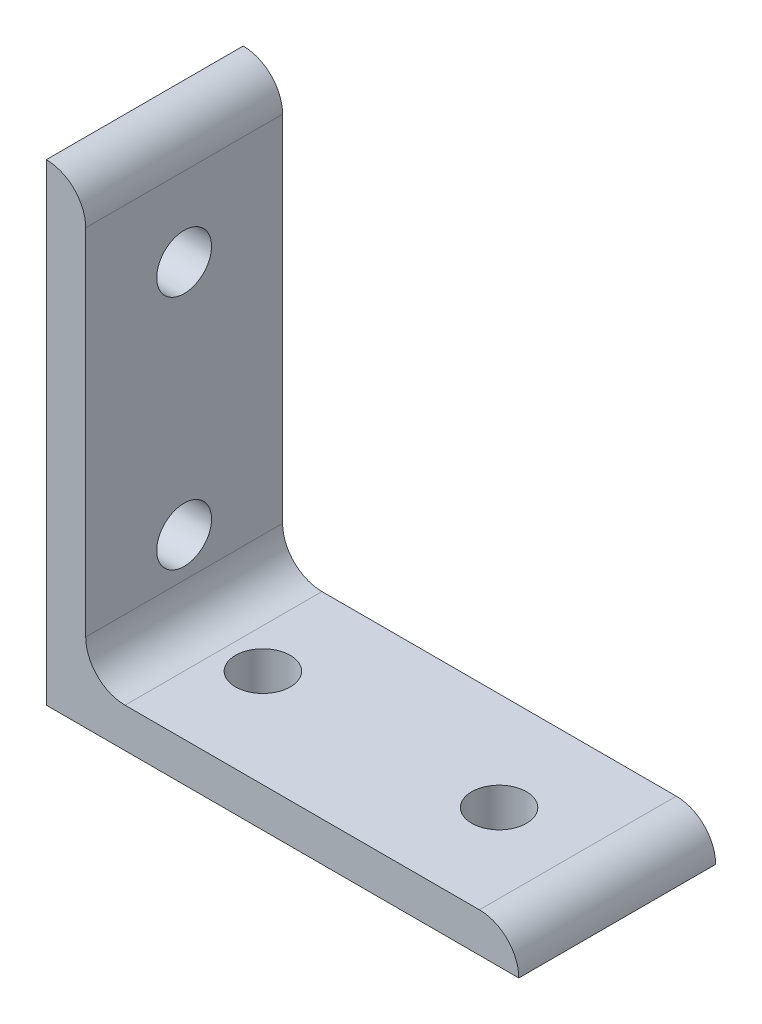
SolidWorks part; units mm, degrees
material "6061 Alloy"
ref_plane "Front Plane" through (0, 0, 0) normal (0, 0, 1) x (1, 0, 0)
ref_plane "Top Plane" through (0, 0, 0) normal (0, 1, 0) x (1, 0, 0)
ref_plane "Right Plane" through (0, 0, 0) normal (1, 0, 0) x (0, 0, -1)
sketch "Sketch1" plane through (0, 0, 0) normal (0, 0, 1) x (1, 0, 0)
  line L1 (0, 0) -> (76.2, 0)
  line L2 (0, 0) -> (0, 76.2)
  line L7 (69.85, 6.35) -> (6.35, 6.35)
  line L8 (6.35, 69.85) -> (6.35, 6.35)
  arc A0 (76.2, 0) -> (69.85, 6.35) centre (69.85, 0) ccw
  arc A1 (0, 76.2) -> (6.35, 69.85) centre (0, 69.85) cw
  dimension "D1" = 6.35
  dimension "D2" = 76.2
extrude "Boss-Extrude1" add sketch "Sketch1" along normal mid plane 31.75
hole_wizard "S (0.348) Diameter Hole1" positions "Sketch2" profile "Sketch3" hole size "S" standard "ANSI Inch" end condition through all
sketch "Sketch2" plane through (6.35, 0, 0) normal (1, 0, 0) x (0, 0, -1)
  line L0 (-15.875, 76.2) -> (15.875, 76.2) construction
  line L1 (15.875, 6.35) -> (15.875, 69.85) construction
  point P0 (0, 57.15)
  point P2 (0, 19.05)
  dimension "D1" = 19.05
  dimension "D2" = 38.1
  dimension "D3" = 15.875
sketch "Sketch3" plane through (6.35, 57.15, 0) normal (0, 1, 0) x (0, 0, -1)
  line L0 (0, 0) -> (0, 6.35)
  line L1 (0, 6.35) -> (4.4196, 6.35)
  line L2 (4.4196, 6.35) -> (4.4196, 0)
  line L5 (4.4196, 0) -> (0, 0)
  line L11 (0, -6.35) -> (0, 107.95) construction
  dimension "Thru Hole Dia." = 8.8392
  dimension "Thru Hole Depth" = 6.35
hole_wizard "S (0.348) Diameter Hole2" positions "Sketch4" profile "Sketch5" hole size "S" standard "ANSI Inch" end condition through all
sketch "Sketch4" plane through (0, 6.35, 0) normal (0, 1, 0) x (-1, 0, 0)
  line L0 (-76.2, 15.875) -> (-76.2, -15.875) construction
  line L1 (-69.85, -15.875) -> (-6.35, -15.875) construction
  point P0 (-19.05, 0)
  point P2 (-57.15, 0)
  dimension "D1" = 19.05
  dimension "D2" = 38.1
  dimension "D3" = 15.875
sketch "Sketch5" plane through (19.05, 6.35, 0) normal (1, 0, 0) x (0, 0, 1)
  line L0 (0, 0) -> (0, 6.35)
  line L1 (0, 6.35) -> (4.4196, 6.35)
  line L2 (4.4196, 6.35) -> (4.4196, 0)
  line L5 (4.4196, 0) -> (0, 0)
  line L11 (0, -6.35) -> (0, 107.95) construction
  dimension "Thru Hole Dia." = 8.8392
  dimension "Thru Hole Depth" = 6.35
fillet "Fillet1" radius 6.35 1 edges at (6.35, 6.35, 0)
